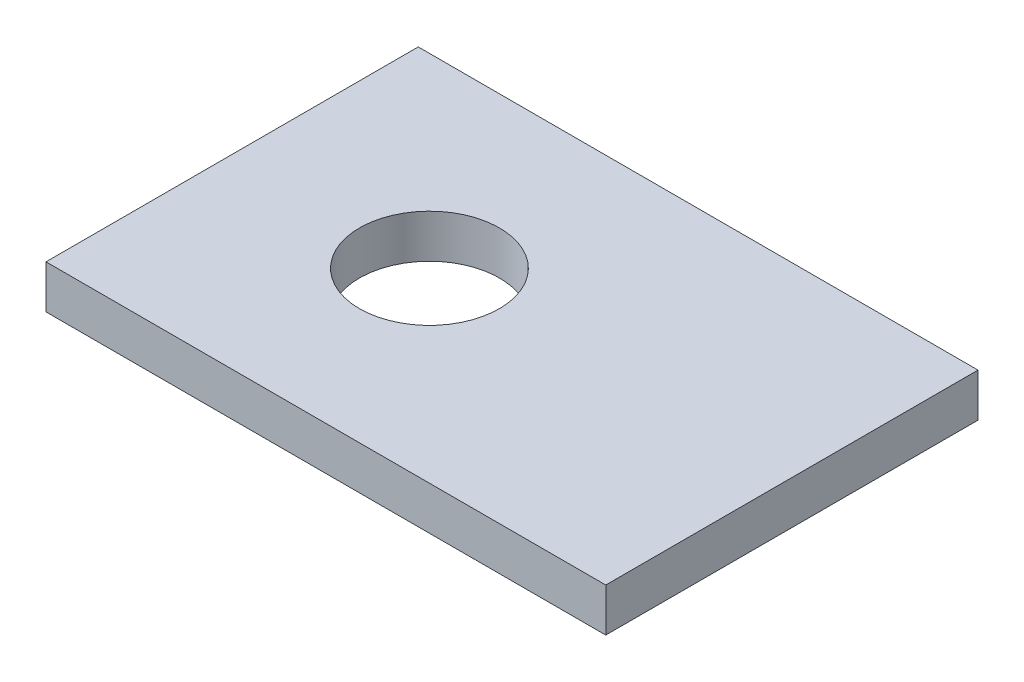
SolidWorks part; units mm, degrees
ref_plane "Front Plane" through (0, 0, 0) normal (0, 0, 1) x (1, 0, 0)
ref_plane "Top Plane" through (0, 0, 0) normal (0, 1, 0) x (1, 0, 0)
ref_plane "Right Plane" through (0, 0, 0) normal (1, 0, 0) x (0, 0, -1)
sketch "Sketch1" plane through (0, 0, 0) normal (0, 0, 1) x (1, 0, 0)
  line L1 (0, 0) -> (20, 0)
  line L2 (0, 0) -> (0, -1.55)
  line L3 (0, -1.55) -> (20, -1.55)
  line L4 (20, 0) -> (20, -1.55)
  dimension "D1" = 1.55
  dimension "D2" = 20
extrude "Boss-Extrude1" add sketch "Sketch1" along normal blind 13.3
sketch "Sketch2" plane through (0, 0, 0) normal (0, 1, 0) x (1, 0, 0)
  circle A0 centre (7.05, -6.65) radius 2.5 construction
  circle A1 centre (7.05, -6.65) radius 2.5
extrude "Cut-Extrude1" cut sketch "Sketch2" against normal blind 10
